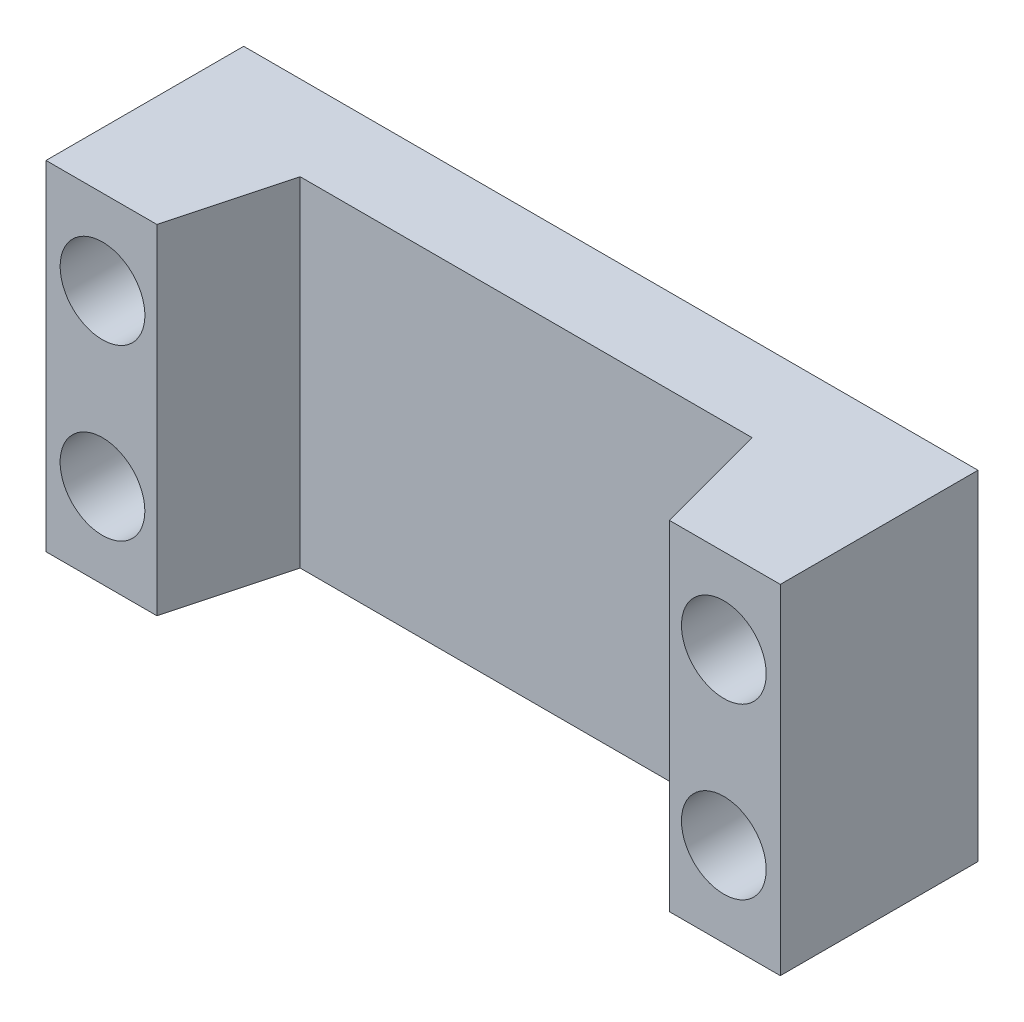
SolidWorks part; units mm, degrees
ref_plane "前视基准面" through (0, 0, 0) normal (0, 0, 1) x (1, 0, 0)
ref_plane "上视基准面" through (0, 0, 0) normal (0, 1, 0) x (1, 0, 0)
ref_plane "右视基准面" through (0, 0, 0) normal (1, 0, 0) x (0, 0, -1)
sketch "草图2" plane through (0, 0, 0) normal (0, 1, 0) x (1, 0, 0)
  line L2 (-1017, 0) -> (-9.0718, 0) construction
  line L3 (-13, 0) -> (-9.0718, 0)
  line L4 (-13, 9) -> (13, 9)
  line L5 (-13, 9) -> (-13, 0)
  line L7 (13, 9) -> (13, 0)
  line L8 (-13, 9) -> (0, 0) construction
  line L9 (0, 0) -> (13, 9) construction
  line L10 (13, 0) -> (9.0718, 0)
  line L11 (0, 9) -> (0, 0) construction
  line L12 (0, 4) -> (0, 4.0099)
  line L13 (-3, 4) -> (4.0753, 4) construction
  line L14 (-8, 4) -> (8, 4)
  line L15 (8, 4) -> (9.0718, 0)
  line L16 (-8, 4) -> (-9.0718, 0)
  line L18 (9.0718, 0) -> (1017.6874, 0) construction
  dimension "D1" = 9
  dimension "D2" = 4
  dimension "D4" = 5
  dimension "D5" = 26
  dimension "D3" = 105
  dimension "D6" = 8
  dimension "D7" = 4
  dimension "D8" = 75
  dimension "D9" = 3.9282
extrude "凸台-拉伸1" add sketch "草图2" along normal blind 12
sketch "草图3" plane through (0, 0, -9) normal (0, 0, -1) x (-1, 0, 0)
  line L1 (-13, 0) -> (13, 0)
  line L2 (-13, 0) -> (-13, 12)
  line L3 (-13, 12) -> (13, 12)
  line L4 (13, 0) -> (13, 12)
extrude "切除-拉伸1" cut sketch "草图3" against normal blind 2
sketch "草图4" plane through (0, 0, -7) normal (0, 0, -1) x (-1, 0, 0)
  line L0 (0, 12) -> (0, 0) construction
  line L1 (13, 12) -> (-13, 12) construction
  line L2 (-13, 0) -> (13, 0) construction
  line L3 (-13, 12) -> (-13, 0) construction
  line L4 (-1000, 6) -> (49000, 6) construction
  circle A0 centre (-11, 3) radius 1.5
  circle A1 centre (11, 3) radius 1.5
  circle A2 centre (11, 9) radius 1.5
  circle A3 centre (-11, 9) radius 1.5
  point P15 (0, 6)
  dimension "D1" = 3
  dimension "D2" = 2
  dimension "D3" = 3
extrude "切除-拉伸2" cut sketch "草图4" against normal blind 7
